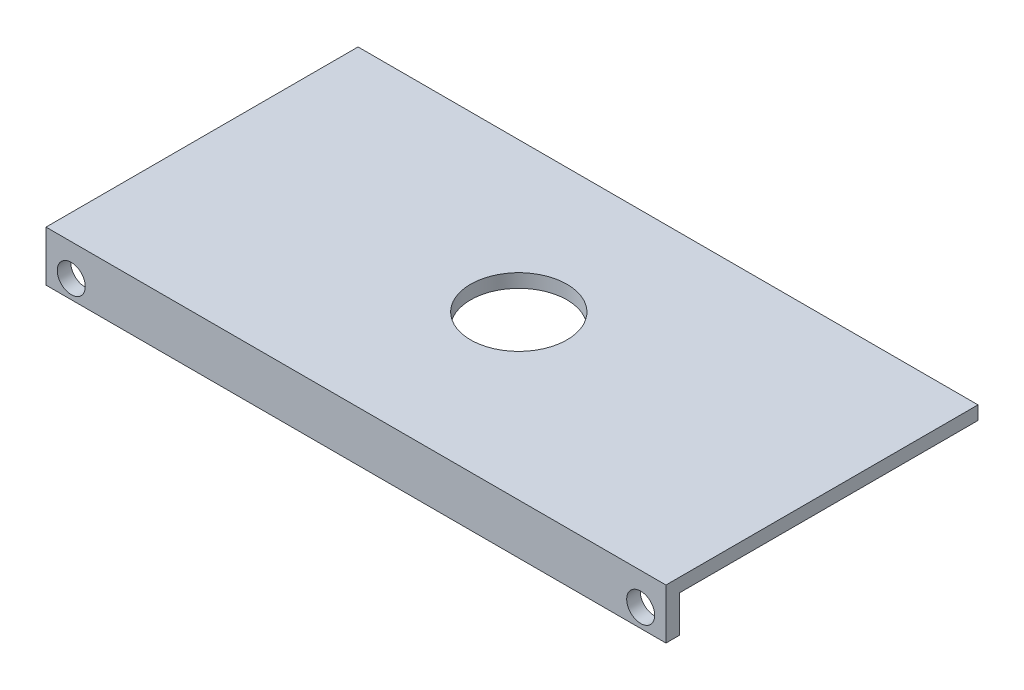
SolidWorks part; units mm, degrees
ref_plane "前视基准面" through (0, 0, 0) normal (0, 0, 1) x (1, 0, 0)
ref_plane "上视基准面" through (0, 0, 0) normal (0, 1, 0) x (1, 0, 0)
ref_plane "右视基准面" through (0, 0, 0) normal (1, 0, 0) x (0, 0, -1)
other "Configuration Table"
sketch "草图1" plane through (0, 0, 0) normal (0, 0, 1) x (1, 0, 0)
  line L1 (34.29, -2.032) -> (-34.29, -2.032)
  line L2 (34.29, -2.032) -> (34.29, 2.032)
  line L3 (34.29, 2.032) -> (-34.29, 2.032)
  line L4 (-34.29, -2.032) -> (-34.29, 2.032)
  line L5 (34.29, -2.032) -> (-34.29, 2.032) construction
  line L6 (34.29, 2.032) -> (-34.29, -2.032) construction
  circle A0 centre (31.496, 0) radius 1.55
  circle A1 centre (-31.496, 0) radius 1.55
  point P0 (0, 0)
  point P10 (-34.29, -0.5799)
  point P13 (-50.3861, 26.0818)
  point P14 (-37.8615, 6.1324)
  point P15 (-49.1862, 18.2445)
  dimension "D3" = 3.1
  dimension "D6" = 2.794
  dimension "D8" = 3.1
  dimension "D1" = 34.29
  dimension "D2" = 2.032
  dimension "D4" = 31.496
  dimension "D5" = 2.794
  dimension "D7" = 31.496
extrude "凸台-拉伸2" add sketch "草图1" along normal blind 1.5 contours A1 | A0 | L3 L4 L1 L2
sketch "草图3" plane through (0, 2.032, 0) normal (0, 1, 0) x (1, 0, 0)
  line L1 (-34.29, 0) -> (34.29, 0)
  line L2 (-34.29, 0) -> (-34.29, -1.5)
  line L3 (-34.29, -1.5) -> (34.29, -1.5)
  line L4 (34.29, 0) -> (34.29, -1.5)
extrude "凸台-拉伸3" add sketch "草图3" along normal blind 1.5
sketch "草图4" plane through (0, 0, 0) normal (0, 0, -1) x (-1, 0, 0)
  line L0 (34.29, -2.032) -> (34.29, 3.532) construction
  line L1 (-34.29, 3.532) -> (34.29, 3.532)
  line L2 (-34.29, 3.532) -> (-34.29, 2.032)
  line L3 (-34.29, 2.032) -> (34.29, 2.032)
  line L4 (34.29, 3.532) -> (34.29, 2.032)
  dimension "D1" = 1.5
extrude "凸台-拉伸4" add sketch "草图4" along normal blind 33.02
sketch "草图5" plane through (0, 2.032, 0) normal (0, -1, 0) x (1, 0, 0)
  line L0 (-34.29, 0) -> (34.29, -33.02) construction
  line L1 (-34.29, 0) -> (34.29, 0)
  line L2 (-34.29, 0) -> (-34.29, -33.02)
  line L3 (-34.29, -33.02) -> (34.29, -33.02)
  line L4 (34.29, 0) -> (34.29, -33.02)
  line L5 (34.29, 0) -> (-34.29, -33.02) construction
  circle A0 centre (0, -16.51) radius 5.334
  dimension "D1" = 10.668
extrude "切除-拉伸2" cut sketch "草图5" against normal blind 33.02 contours A0
